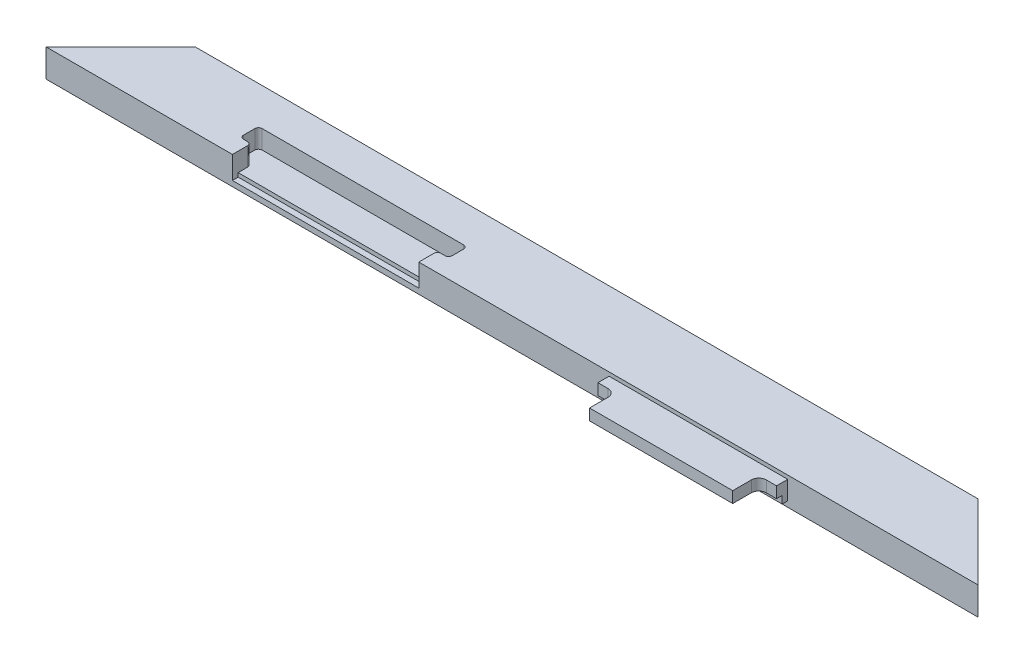
SolidWorks part; units mm, degrees
material "99.5% Aluminum Oxide"
ref_plane "Front Plane" through (0, 0, 0) normal (0, 0, 1) x (1, 0, 0)
ref_plane "Top Plane" through (0, 0, 0) normal (0, 1, 0) x (1, 0, 0)
ref_plane "Right Plane" through (0, 0, 0) normal (1, 0, 0) x (0, 0, -1)
sketch "Sketch1" plane through (0, 0, 0) normal (0, 1, 0) x (1, 0, 0)
  line L1 (-125, -10) -> (125, -10)
  line L2 (-125, -10) -> (-125, 10) construction
  line L3 (-105, 10) -> (105, 10)
  line L4 (125, -10) -> (125, 10) construction
  line L5 (-125, -10) -> (125, 10) construction
  line L6 (-125, 10) -> (125, -10) construction
  line L8 (-125, -10) -> (-105, 10)
  line L9 (125, -10) -> (105, 10)
  line L10 (-125, 10) -> (-105, 10) construction
  line L11 (105, 10) -> (125, 10) construction
  point P0 (0, 0)
  dimension "D1" = 250
  dimension "D2" = 20
  dimension "D3" = 45
  dimension "D4" = 45
extrude "Boss-Extrude1" add sketch "Sketch1" along normal mid plane 7.5
ref_plane "Plane1" through (0, 2.75, 0) normal (0, -1, 0) x (-1, 0, 0)
sketch "Sketch3" plane through (0, 2.75, 0) normal (0, 1, 0) x (-1, 0, 0)
  line L0 (125, 10) -> (-125, 10) construction
  line L2 (-75, 10) -> (-75, 20) construction
  line L3 (-69.2063, 20) -> (-30.7938, 20)
  line L5 (-50, 20) -> (-50, 10) construction
  line L6 (-73.9563, 10) -> (-73.9563, 13)
  line L7 (-73.9563, 13) -> (-69.2063, 13)
  line L8 (-69.2063, 13) -> (-69.2063, 20)
  line L9 (-30.7938, 13) -> (-30.7938, 20)
  line L10 (-26.0438, 13) -> (-30.7938, 13)
  line L11 (-26.0438, 10) -> (-26.0438, 13)
  line L12 (125, 10) -> (-125, 10) construction
  line L13 (-73.9563, 10) -> (-26.0438, 10)
  point P6 (-125, 10)
  dimension "D1" = 50
  dimension "D3" = 10
  dimension "D4" = 1.0437
  dimension "D5" = 3
  dimension "D6" = 4.75
  dimension "D7" = 38.4125
extrude "Boss-Extrude3" add sketch "Sketch3" against normal blind 3
sketch "Sketch8" plane through (0, -0.25, 0) normal (0, -1, 0) x (1, 0, 0)
  line L0 (73.9563, 13) -> (73.9563, 10) construction
  line L1 (26.0438, 10) -> (73.9563, 10)
  line L2 (26.0438, 10) -> (26.0438, 11.5)
  line L3 (26.0438, 11.5) -> (73.9563, 11.5)
  line L4 (73.9563, 10) -> (73.9563, 11.5)
extrude "Boss-Extrude5" add sketch "Sketch8" along normal blind 2
fillet "Fillet4" radius 2
sketch "Sketch4" plane through (0, 2.75, 0) normal (0, 1, 0) x (-1, 0, 0)
  line L0 (125, 10) -> (-125, 10) construction
  line L5 (50, 0) -> (50, 10) construction
  line L6 (22, 0) -> (78, 0)
  line L7 (0, 0) -> (0, 192.9173) construction
  line L10 (75, 10) -> (25, 10)
  line L12 (-26.0438, 10) -> (-26.0438, 13)
  line L13 (-73.9563, 10) -> (-26.0438, 10)
  line L14 (-26.0438, 10) -> (-26.0438, 13)
  line L15 (-30.7938, 20) -> (-69.2063, 20)
  line L17 (-73.9563, 10) -> (-26.0438, 10) construction
  line L19 (-30.7938, 20) -> (-69.2063, 20) construction
  line L21 (78, 0) -> (78, 5)
  line L22 (78, 5) -> (75, 5)
  line L23 (75, 5) -> (75, 10)
  line L24 (25, 5) -> (25, 10)
  line L25 (22, 5) -> (25, 5)
  line L26 (22, 0) -> (22, 5)
  line L28 (-26.0438, 13) -> (-28.7938, 13)
  line L29 (-26.0438, 13) -> (-28.7938, 13)
  line L30 (-30.7938, 15) -> (-30.7938, 20)
  line L31 (-30.7938, 15) -> (-30.7938, 20)
  line L32 (-69.2063, 20) -> (-69.2063, 15)
  line L33 (-69.2063, 20) -> (-69.2063, 15)
  line L34 (-71.2063, 13) -> (-73.9563, 13)
  line L35 (-71.2063, 13) -> (-73.9563, 13)
  line L36 (-73.9563, 13) -> (-73.9563, 10)
  line L37 (-73.9563, 13) -> (-73.9563, 10)
  arc A4 (-30.7938, 15) -> (-28.7938, 13) centre (-28.7938, 15) ccw
  arc A5 (-30.7938, 15) -> (-28.7938, 13) centre (-28.7938, 15) ccw
  arc A6 (-71.2063, 13) -> (-69.2063, 15) centre (-71.2063, 15) ccw
  arc A7 (-71.2063, 13) -> (-69.2063, 15) centre (-71.2063, 15) ccw
  dimension "D2" = 5
  dimension "D1" = 0
  dimension "D3" = 3
  dimension "D4" = 10
  dimension "D5" = 50
  dimension "D6" = 50
extrude "Cut-Extrude1" cut sketch "Sketch4" against normal blind 4 and the other way through all contours L6 L26 L25 L24 L10 L23 L22 L21
sketch "Sketch9" plane through (0, -1.25, 0) normal (0, 1, 0) x (1, 0, 0)
  line L0 (-75, -5) -> (-75, -10) construction
  line L1 (-25, -10) -> (-75, -10)
  line L2 (-25, -10) -> (-25, -8.45)
  line L3 (-25, -8.45) -> (-75, -8.45)
  line L4 (-75, -10) -> (-75, -8.45)
  dimension "D1" = 1.55
extrude "Cut-Extrude2" cut sketch "Sketch9" against normal blind 1.05 contours L3 L4 L1 L2
fillet "Fillet6" radius 1
chamfer "Chamfer1" distance 5 angle 45
shell "Shell1" [suppressed] thickness 2.5
sketch "Sketch6" [suppressed] plane through (0, 3.75, 0) normal (0, -1, 0) x (1, 0, 0)
  line L0 (-17.2839, 7.5) -> (-17.2839, -7.5)
  line L3 (-62.983, 7.5) -> (118.9645, 7.5) construction
  line L4 (-18.5508, 7.5) -> (-17.2839, 7.5)
  line L5 (-24.5823, -7.5) -> (-17.2839, -7.5)
  line L6 (-50, -5) -> (-50, 27.6649) construction
  line L7 (-25, -5) -> (-75, -5) construction
  line L8 (-75.4177, -7.5) -> (-82.7161, -7.5)
  line L9 (-81.4492, 7.5) -> (-82.7161, 7.5)
  line L10 (-82.7161, 7.5) -> (-82.7161, -7.5)
  line L11 (-118.9645, 7.5) -> (-81.4492, 7.5) construction
  line L12 (103.9645, -7.5) -> (-24.5823, -7.5) construction
  arc A1 (-24.5823, -7.5) -> (-18.5508, 7.5) centre (-27.7839, 2.5) ccw
  arc A2 (-75.4177, -7.5) -> (-81.4492, 7.5) centre (-72.2161, 2.5) cw
  arc A3 (-24.5823, -7.5) -> (-18.5508, 7.5) centre (-27.7839, 2.5) ccw construction
  line M32 (-24.5823, -7.5) -> (103.9645, -7.5)
  line M34 (118.9645, 7.5) -> (-18.5508, 7.5)
  arc M35 (-18.5508, 7.5) -> (-24.5823, -7.5) centre (-27.7839, 2.5) cw
  line M44 (-103.9645, -7.5) -> (-75.4177, -7.5)
  arc M45 (-75.4177, -7.5) -> (-81.4492, 7.5) centre (-72.2161, 2.5) cw
  line M46 (-81.4492, 7.5) -> (-118.9645, 7.5)
extrude "Boss-Extrude4" [suppressed] add sketch "Sketch6" along normal up to next contours L0 M35 M32 | L0 M34 M35 | L10 M46 M45 | L10 M45 M44
sketch "Sketch5" [suppressed] plane through (0, 3.75, 0) normal (0, -1, 0) x (1, 0, 0)
  line L0 (118.9645, 7.5) -> (103.9645, -7.5) construction
  line L2 (103.9645, -7.5) -> (-17.2839, -7.5) construction
  line L3 (118.9645, 7.5) -> (103.9645, -7.5) construction
  line L4 (-17.001, 7.5) -> (118.9645, 7.5) construction
  line L5 (103.9645, -7.5) -> (-17.4902, -7.5) construction
  line L6 (75, 7.5) -> (75, -7.5)
  line L7 (75, 24.1468) -> (75, 10.8532) construction
  line L8 (25, 7.5) -> (25, -7.5)
  line L9 (25, 10.8532) -> (25, 24.1468) construction
rib "Rib1" [suppressed] sketch "Sketch5" sketch "Sketch5" thickness 5 extrusion direction normal to sketch draft on no parameters "D1"=5
fillet "Fillet1" [suppressed] radius 1
ref_plane "Plane2" through (50, 0, 0) normal (-1, 0, 0) x (0, 0, 1)
